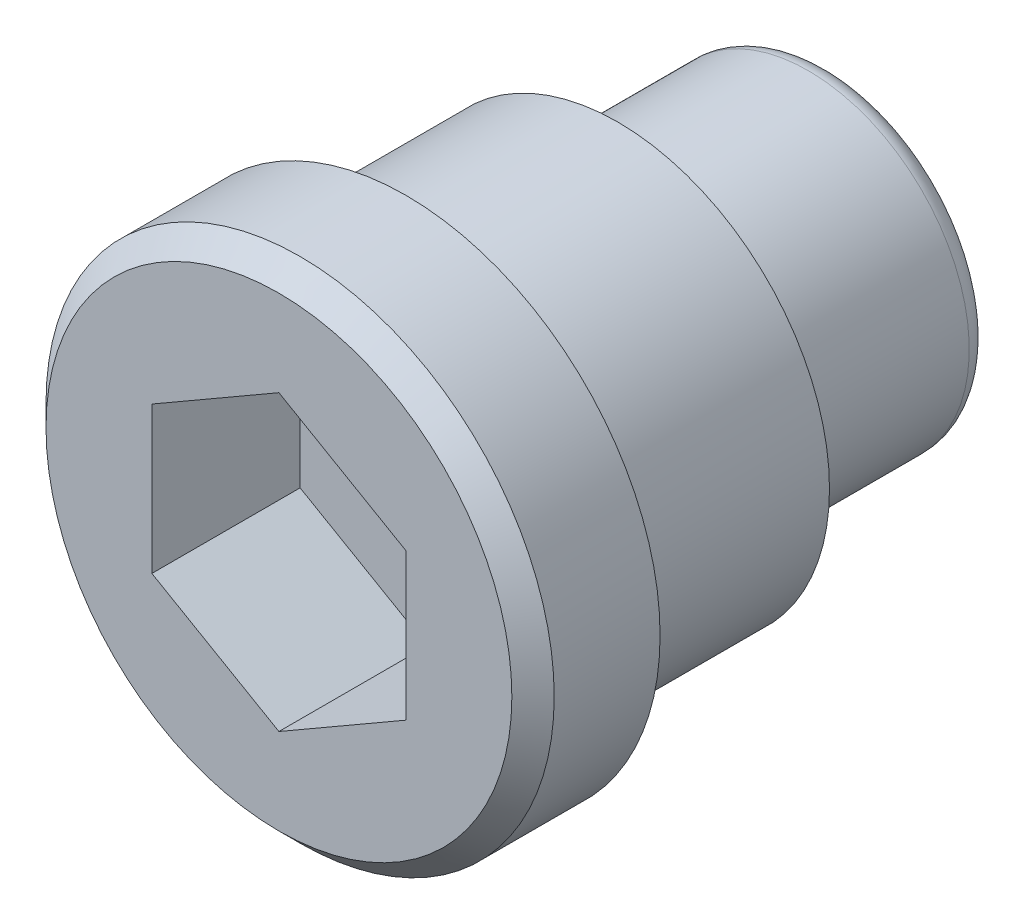
SolidWorks part; units mm, degrees
ref_plane "Front Plane" through (0, 0, 0) normal (0, 0, 1) x (1, 0, 0)
ref_plane "Top Plane" through (0, 0, 0) normal (0, 1, 0) x (1, 0, 0)
ref_plane "Right Plane" through (0, 0, 0) normal (1, 0, 0) x (0, 0, -1)
ref_plane "Plane1" through (0, 0, 0) normal (0, -1, 0) x (1, 0, 0)
sketch "Sketch1" plane through (0, 0, 0) normal (0, -1, 0) x (1, 0, 0)
  line L0 (5.5, 0) -> (0, 0)
  line L1 (0, 0) -> (0, -3)
  line L2 (0, -3) -> (6, -3)
  line L3 (6, -3) -> (6, -0.5)
  line L4 (6, -0.5) -> (5.5, 0)
  line L5 (0, 0) -> (0, -3) construction
revolve "Revolve1" add sketch "Sketch1" angle 360 about L5
sketch "Sketch2" plane through (0, 0, -3) normal (0, 0, -1) x (-1, 0, 0)
  circle A0 centre (0, 0) radius 5
extrude "Boss-Extrude1" add sketch "Sketch2" along normal blind 5
sketch "Sketch3" plane through (0, 0, -8) normal (0, 0, -1) x (-1, 0, 0)
  circle A0 centre (0, 0) radius 3.8
extrude "Boss-Extrude2" add sketch "Sketch3" along normal blind 5
sketch "Sketch4" plane through (0, 0, 0) normal (0, 0, 1) x (1, 0, 0)
  line L0 (3, 1.7321) -> (0, 3.4641)
  line L1 (0, 3.4641) -> (-3, 1.7321)
  line L2 (-3, 1.7321) -> (-3, -1.7321)
  line L3 (-3, -1.7321) -> (0, -3.4641)
  line L4 (0, -3.4641) -> (3, -1.7321)
  line L5 (3, -1.7321) -> (3, 1.7321)
extrude "Cut-Extrude1" cut sketch "Sketch4" against normal blind 3.5
fillet "Fillet1" radius 0.5 1 edges at (-3.8, 0, -13)
